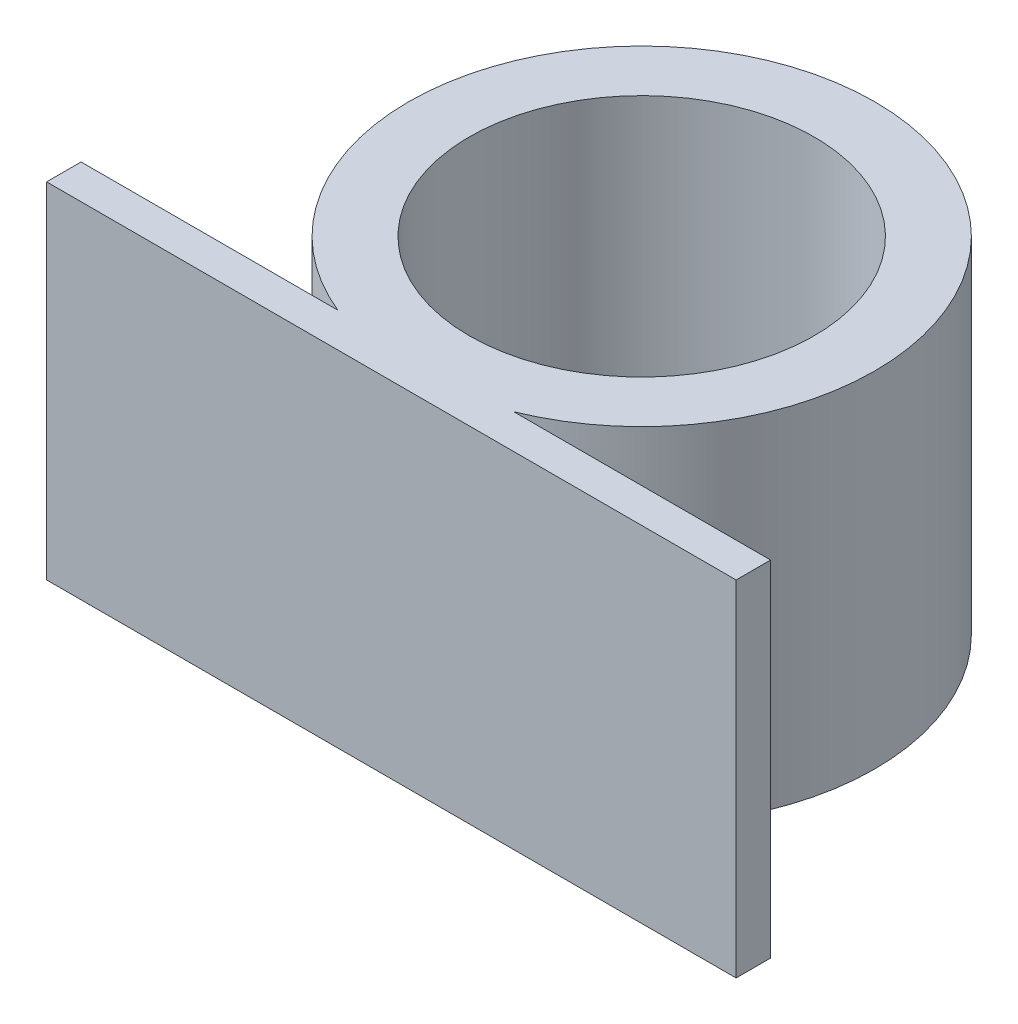
SolidWorks part; units mm, degrees
ref_plane "Front Plane" through (0, 0, 0) normal (0, 0, 1) x (1, 0, 0)
ref_plane "Top Plane" through (0, 0, 0) normal (0, 1, 0) x (1, 0, 0)
ref_plane "Right Plane" through (0, 0, 0) normal (1, 0, 0) x (0, 0, -1)
sketch "Sketch1" plane through (0, 0, 0) normal (0, 1, 0) x (1, 0, 0)
  line L5 (5.1037, -12.5241) -> (20, -12.5241)
  line L6 (-20, -12.5241) -> (-5.1037, -12.5241)
  line L7 (-20, -12.5241) -> (-20, -14.5241)
  line L8 (-20, -14.5241) -> (20, -14.5241)
  line L9 (20, -12.5241) -> (20, -14.5241)
  circle A0 centre (0, 0) radius 10
  arc A1 (5.1037, -12.5241) -> (-5.1037, -12.5241) centre (0, 0) ccw
  point P4 (0, -13.5241)
  dimension "D1" = 2
  dimension "D3" = 20
  dimension "D2" = 40
extrude "Boss-Extrude1" add sketch "Sketch1" along normal blind 20
